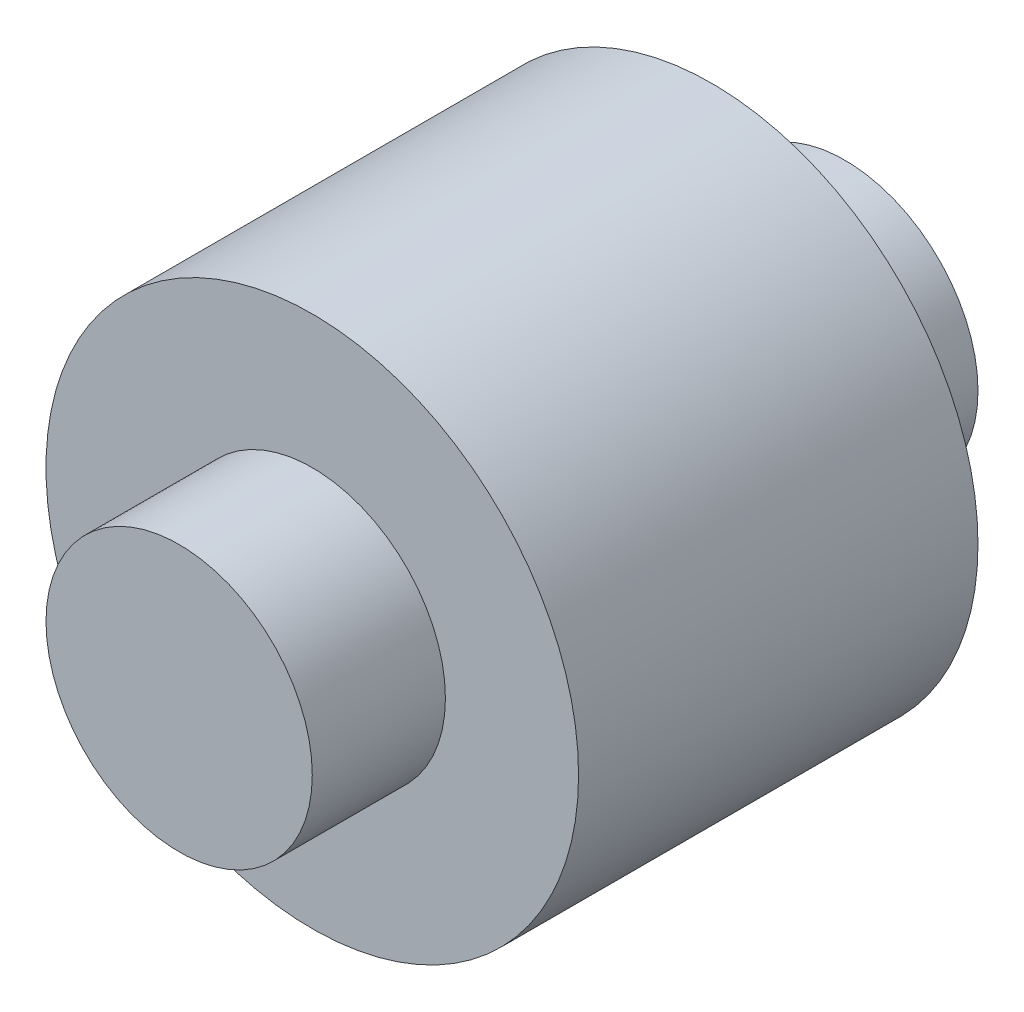
SolidWorks part; units mm, degrees
ref_plane "정면" through (0, 0, 0) normal (0, 0, 1) x (1, 0, 0)
ref_plane "윗면" through (0, 0, 0) normal (0, 1, 0) x (1, 0, 0)
ref_plane "우측면" through (0, 0, 0) normal (1, 0, 0) x (0, 0, -1)
sketch "스케치1" plane through (0, 0, 0) normal (0, 0, 1) x (1, 0, 0)
  circle A0 centre (0, 0) radius 10
  dimension "D1" = 20
extrude "보스-돌출1" add sketch "스케치1" along normal blind 15
sketch "스케치2" plane through (0, 0, 15) normal (0, 0, 1) x (1, 0, 0)
  circle A0 centre (0, 0) radius 5
  dimension "D1" = 10
extrude "보스-돌출2" add sketch "스케치2" along normal blind 5
ref_plane "평면1" through (0, 0, 7.5) normal (0, 0, -1) x (-1, 0, 0)
mirror "대칭 복사1" about plane through (0, 0, 7.5) normal (0, 0, -1) of "보스-돌출2"
